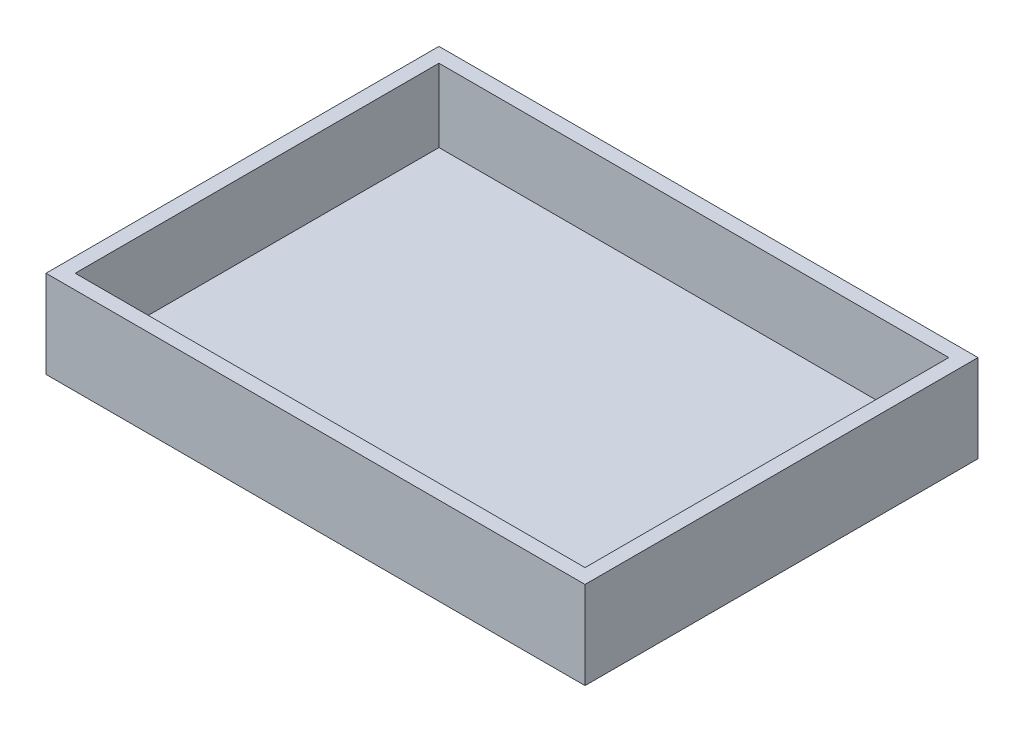
SolidWorks part; units mm, degrees
ref_plane "Front Plane" through (0, 0, 0) normal (0, 0, 1) x (1, 0, 0)
ref_plane "Top Plane" through (0, 0, 0) normal (0, 1, 0) x (1, 0, 0)
ref_plane "Right Plane" through (0, 0, 0) normal (1, 0, 0) x (0, 0, -1)
sketch "Sketch1" plane through (0, 0, 0) normal (0, 1, 0) x (1, 0, 0)
  line L0 (-36.9, -26.9) -> (-36.9, 26.9)
  line L1 (-34.9, -24.9) -> (34.9, -24.9)
  line L2 (-34.9, -24.9) -> (-34.9, 24.9)
  line L3 (-34.9, 24.9) -> (34.9, 24.9)
  line L4 (34.9, -24.9) -> (34.9, 24.9)
  line L5 (-34.9, -24.9) -> (34.9, 24.9) construction
  line L6 (-34.9, 24.9) -> (34.9, -24.9) construction
  line L7 (-36.9, 26.9) -> (36.9, 26.9)
  line L8 (36.9, -26.9) -> (36.9, 26.9)
  line L9 (-36.9, -26.9) -> (36.9, -26.9)
  point P0 (0, 0)
  dimension "D1" = 69.8
  dimension "D2" = 49.8
  dimension "D3" = 2
extrude "Boss-Extrude1" add sketch "Sketch1" along normal blind 10 contours L0 L7 L8 L9
sketch "Sketch2" plane through (0, 0, 0) normal (0, -1, 0) x (1, 0, 0)
  line L1 (-36.9, 26.9) -> (36.9, 26.9)
  line L2 (-36.9, 26.9) -> (-36.9, -26.9)
  line L3 (-36.9, -26.9) -> (36.9, -26.9)
  line L4 (36.9, 26.9) -> (36.9, -26.9)
extrude "Boss-Extrude2" add sketch "Sketch2" along normal blind 2
